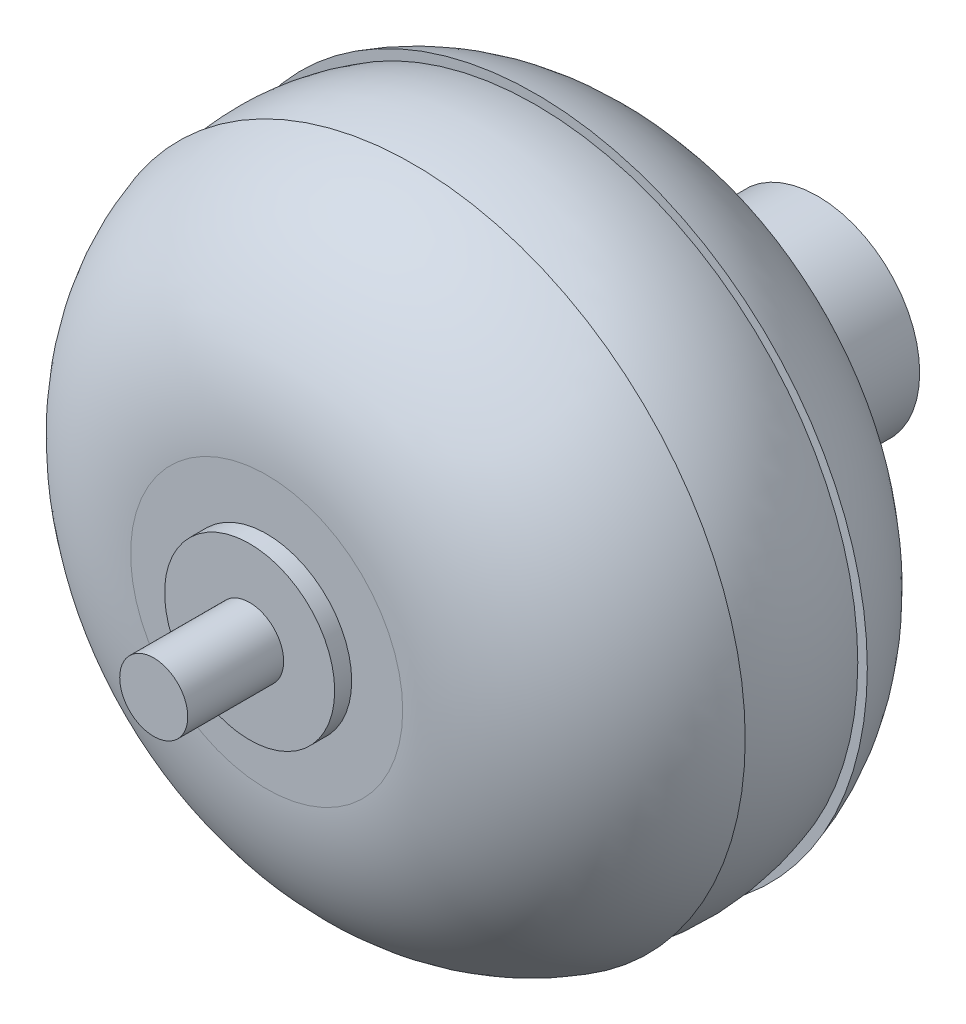
SolidWorks part; units mm, degrees
ref_plane "Front Plane" through (0, 0, 0) normal (0, 0, 1) x (1, 0, 0)
ref_plane "Top Plane" through (0, 0, 0) normal (0, 1, 0) x (1, 0, 0)
ref_plane "Right Plane" through (0, 0, 0) normal (1, 0, 0) x (0, 0, -1)
sketch "Sketch1" plane through (0, 0, 0) normal (0, 0, 1) x (1, 0, 0)
  circle A0 centre (0, 0) radius 10
extrude "Boss-Extrude1" add sketch "Sketch1" along normal blind 12.2
sketch "Sketch4" plane through (0, 0, 12.2) normal (0, 0, 1) x (1, 0, 0)
  circle A0 centre (0, 0) radius 2.5
extrude "Boss-Extrude3" add sketch "Sketch4" along normal blind 0.5
sketch "Sketch5" plane through (0, 0, 12.2) normal (0, 0, 1) x (1, 0, 0)
  circle A0 centre (0, 0) radius 1
extrude "Boss-Extrude4" add sketch "Sketch5" along normal blind 3.32
fillet "Fillet1" radius 6 2 edges at (10, 0, 12.2) (10, 0, 0)
sketch "Sketch2" plane through (0, 0, 0) normal (0, 0, -1) x (-1, 0, 0)
  circle A0 centre (0, 0) radius 3
  dimension "D1" = 6
extrude "Boss-Extrude2" add sketch "Sketch2" along normal blind 4
sketch "Sketch6" plane through (0, 0, -4) normal (0, 0, -1) x (-1, 0, 0)
  circle A0 centre (0, 0) radius 2.25
  dimension "D1" = 4.5
extrude "Cut-Extrude1" cut sketch "Sketch6" against normal blind 2.55
sketch "Sketch7" plane through (0, 0, 0) normal (1, 0, 0) x (0, 0, -1)
  line L0 (-15.1934, 0) -> (8.0917, 0) construction
  line L1 (-7.8873, 10.5991) -> (-4.2911, 10.5991)
  line L2 (-7.8873, 10.5991) -> (-7.8873, 9.4712)
  line L4 (-4.2911, 10.5991) -> (-4.2911, 9.4712)
  arc A0 (-7.8873, 9.4712) -> (-4.2911, 9.4712) centre (-6.0892, 3.9749) cw
  dimension "D1" = 3.5962
revolve "Cut-Revolve1" cut sketch "Sketch7" angle 360 about L0
